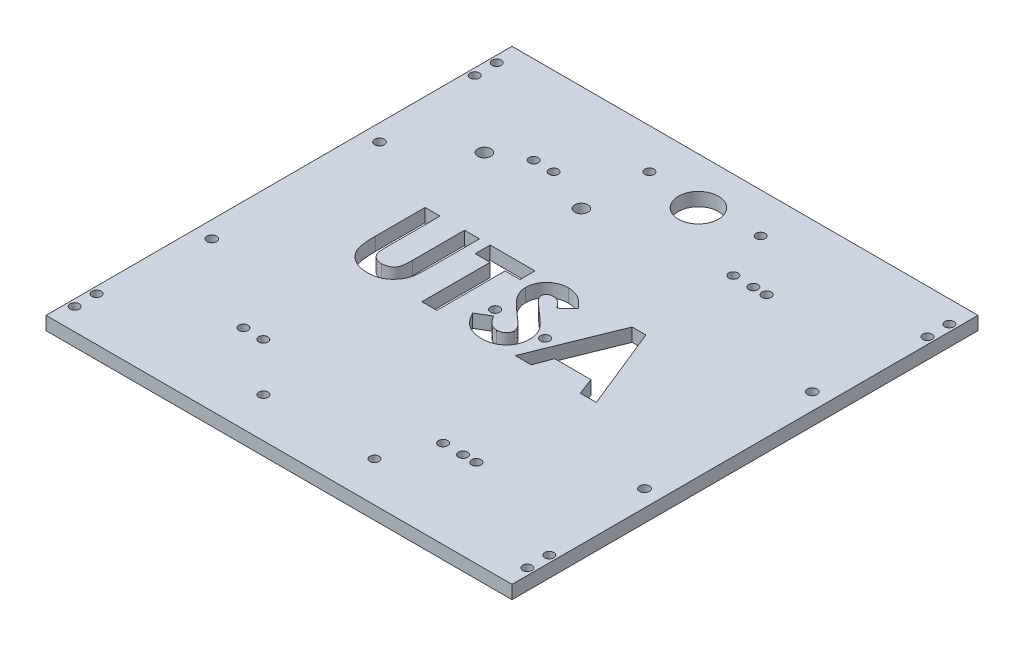
SolidWorks part; units mm, degrees
ref_plane "Front Plane" through (0, 0, 0) normal (0, 0, 1) x (1, 0, 0)
ref_plane "Top Plane" through (0, 0, 0) normal (0, 1, 0) x (1, 0, 0)
ref_plane "Right Plane" through (0, 0, 0) normal (1, 0, 0) x (0, 0, -1)
sketch "Sketch1" plane through (0, 0, 0) normal (0, 1, 0) x (1, 0, 0)
  line L1 (-101.1115, 43.9615) -> (76.6885, 43.9615)
  line L2 (-101.1115, 43.9615) -> (-101.1115, -133.8385)
  line L3 (-101.1115, -133.8385) -> (76.6885, -133.8385)
  line L4 (76.6885, 43.9615) -> (76.6885, -133.8385)
  dimension "D1" = 177.8
  dimension "D2" = 76.6885
  dimension "D3" = 43.9615
extrude "Boss-Extrude2" add sketch "Sketch1" along normal blind 5.08 contours L4 L1 L2 L3
sketch "Sketch4" plane through (0, 0, 0) normal (0, 1, 0) x (1, 0, 0)
  text T0 "UTSA" font "Century Gothic" height in points 120
  dimension "D1" = 101.6
  dimension "D2" = 33.02
extrude "Cut-Extrude1" cut sketch "Sketch4" against normal blind 72.39 and the other way blind 96.266
sketch "Sketch5" plane through (0, 0, 0) normal (0, 1, 0) x (1, 0, 0)
  line L0 (-12.2115, 43.9615) -> (-12.2115, -160.5771) construction
  line L1 (-101.1115, 43.9615) -> (76.6885, 43.9615) construction
  line L2 (-101.1115, -44.9385) -> (114.2809, -44.9385) construction
  line L3 (-101.1115, 43.9615) -> (-101.1115, -133.8385) construction
  circle A0 centre (-98.5715, 35.5795) radius 1.7526
  circle A1 centre (-98.5715, 27.1975) radius 1.7526
  circle A2 centre (74.1485, 27.1975) radius 1.7526
  circle A3 centre (74.1485, 35.5795) radius 1.7526
  circle A4 centre (-98.5715, -125.4565) radius 1.7526
  circle A5 centre (-98.5715, -117.0745) radius 1.7526
  circle A6 centre (74.1485, -125.4565) radius 1.7526
  circle A7 centre (74.1485, -117.0745) radius 1.7526
  dimension "D1" = 3.5052
  dimension "D2" = 2.54
  dimension "D3" = 8.382
  dimension "D4" = 8.382
extrude "Cut-Extrude2" cut sketch "Sketch5" along normal blind 37.084
sketch "Sketch6" plane through (0, 0, 0) normal (0, 1, 0) x (1, 0, 0)
  line L0 (-12.2115, -133.8385) -> (-12.2115, 63.9632) construction
  line L1 (-101.1115, -133.8385) -> (76.6885, -133.8385) construction
  circle A0 centre (70.3385, -76.9385) radius 1.85
  circle A1 centre (70.3385, -12.9385) radius 1.85
  circle A2 centre (-94.7615, -12.9385) radius 1.85
  circle A3 centre (-94.7615, -76.9385) radius 1.85
  dimension "D1" = 3.7
extrude "Cut-Extrude3" cut sketch "Sketch6" along normal blind 14.478
sketch "Sketch7" plane through (0, 0, 0) normal (0, 1, 0) x (1, 0, 0)
  circle A0 centre (-59.3267, -100.3232) radius 1.7526
  circle A1 centre (-51.7067, -100.3232) radius 1.7526
  circle A2 centre (16.8733, -100.3232) radius 1.7526
  circle A3 centre (24.4933, -100.3232) radius 1.7526
  dimension "D1" = 3.5052
extrude "Cut-Extrude4" cut sketch "Sketch7" along normal blind 228.6
sketch "Sketch8" plane through (0, 0, 0) normal (0, 1, 0) x (1, 0, 0)
  line L0 (-101.1115, 43.9615) -> (76.6885, 43.9615) construction
  circle A0 centre (-12.2115, 26.1815) radius 7.62
  dimension "D1" = 17.78
  dimension "D2" = 15.24
  dimension "D3" = 12.2115
extrude "Cut-Extrude6" cut sketch "Sketch8" along normal blind 20.574
sketch "Sketch9" plane through (0, 0, 0) normal (0, 1, 0) x (1, 0, 0)
  line L0 (-101.1115, 43.9615) -> (76.6885, 43.9615) construction
  line L1 (-101.1115, -44.9385) -> (82.7878, -44.9385) construction
  line L2 (-101.1115, 43.9615) -> (-101.1115, -133.8385) construction
  circle A0 centre (-33.4187, 28.7215) radius 1.7526
  circle A1 centre (8.9957, 28.7215) radius 1.7526
  circle A2 centre (8.9957, -118.5985) radius 1.7526
  circle A3 centre (-33.4187, -118.5985) radius 1.7526
  dimension "D1" = 3.5052
  dimension "D2" = 15.24
  dimension "D3" = 8.9957
  dimension "D4" = 33.4187
extrude "Cut-Extrude7" cut sketch "Sketch9" along normal blind 15.748
sketch "Sketch10" plane through (0, 0, 0) normal (0, 1, 0) x (1, 0, 0)
  circle A0 centre (-17.336, -46.2402) radius 1.778
  dimension "D1" = 3.556
extrude "Cut-Extrude8" cut sketch "Sketch10" along normal blind 46.482
sketch "Sketch11" plane through (0, 0, 0) normal (0, 1, 0) x (1, 0, 0)
  circle A0 centre (1.714, -46.2402) radius 1.778
  dimension "D1" = 3.556
extrude "Cut-Extrude9" cut sketch "Sketch11" along normal blind 29.21
sketch "Sketch12" plane through (0, 0, 0) normal (0, 1, 0) x (1, 0, 0)
  circle A1 centre (29.5733, -100.3232) radius 1.778
  dimension "D1" = 3.556
extrude "Cut-Extrude11" cut sketch "Sketch12" along normal blind 19.05
sketch "Sketch13" plane through (0, 0, 0) normal (0, 1, 0) x (1, 0, 0)
  circle A0 centre (-71.2692, 3.5865) radius 2.5
  circle A1 centre (-34.2692, 3.5865) radius 2.5
  dimension "D1" = 5
extrude "Cut-Extrude12" cut sketch "Sketch13" along normal blind 15.494
sketch "Sketch14" plane through (0, 0, 0) normal (0, 1, 0) x (1, 0, 0)
  line L0 (-101.1115, -44.9385) -> (94.426, -44.9385) construction
  line L1 (-101.1115, 43.9615) -> (-101.1115, -133.8385) construction
  circle A0 centre (-59.3267, -100.3232) radius 1.7526
  circle A5 centre (-51.7067, -100.3232) radius 1.7526
  circle A6 centre (16.8733, -100.3232) radius 1.7526
  circle A7 centre (24.4933, -100.3232) radius 1.7526
  circle A8 centre (24.4933, 10.4463) radius 1.7526
  circle A9 centre (16.8733, 10.4463) radius 1.7526
  circle A10 centre (-51.7067, 10.4463) radius 1.7526
  circle A11 centre (-59.3267, 10.4463) radius 1.7526
  circle A12 centre (29.5733, -100.3232) radius 1.778
  circle A13 centre (29.5733, 10.4463) radius 1.778
  dimension "D1" = 3.5052
  dimension "D2" = 3.556
extrude "Cut-Extrude13" cut sketch "Sketch14" along normal blind 19.304
sketch "Sketch15" plane through (0, 0, 0) normal (0, 1, 0) x (1, 0, 0)
  line L0 (14.7715, -31.5066) -> (8.8815, -48.0548)
  line L1 (8.8815, -48.0548) -> (26.1309, -48.0548)
  line L2 (26.1309, -48.0548) -> (19.3994, -31.5066)
  line L3 (19.3994, -31.5066) -> (14.7715, -31.5066)
  dimension "D1" = 8.8815
  dimension "D2" = 14.7715
  dimension "D3" = 19.3994
  dimension "D4" = 26.1309
  dimension "D5" = 31.5066
  dimension "D6" = 48.0548
extrude "Cut-Extrude14" cut sketch "Sketch15" along normal blind 27.432
